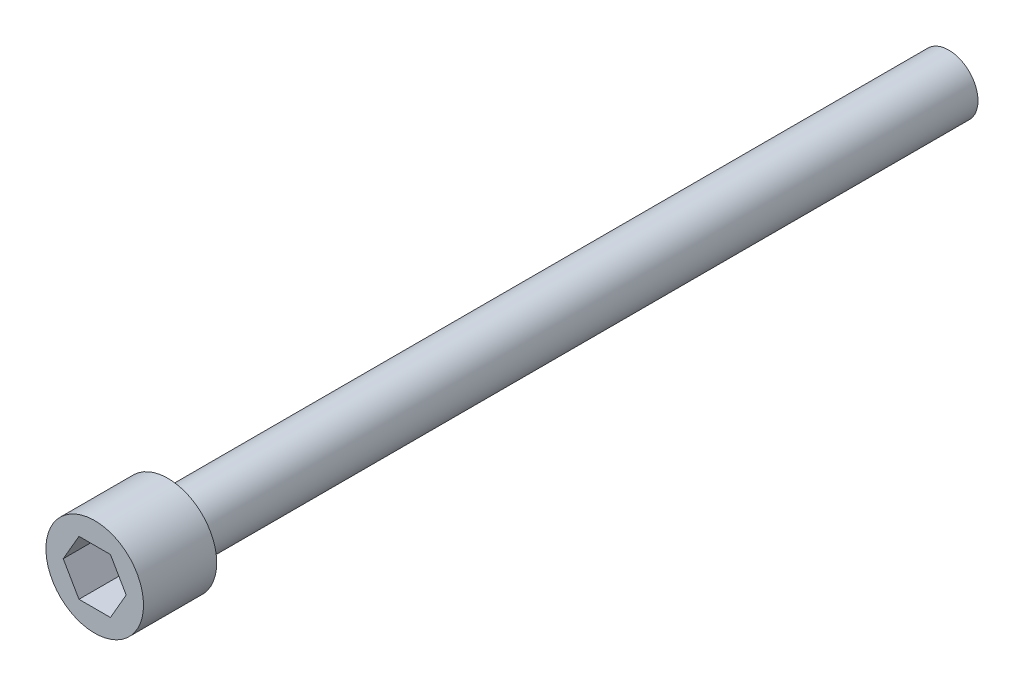
SolidWorks part; units mm, degrees
ref_plane "Front Plane" through (0, 0, 0) normal (0, 0, 1) x (1, 0, 0)
ref_plane "Top Plane" through (0, 0, 0) normal (0, 1, 0) x (1, 0, 0)
ref_plane "Right Plane" through (0, 0, 0) normal (1, 0, 0) x (0, 0, -1)
sketch "Sketch1" plane through (0, 0, 0) normal (0, 0, 1) x (1, 0, 0)
  circle A0 centre (-15, 15) radius 1.2
extrude "Boss-Extrude1" add sketch "Sketch1" against normal blind 32
sketch "Sketch2" plane through (0, 0, 0) normal (0, 0, 1) x (1, 0, 0)
  circle A0 centre (-15, 15) radius 2
extrude "Boss-Extrude2" add sketch "Sketch2" along normal blind 3
sketch "Sketch3" plane through (0, 0, 3) normal (0, 0, 1) x (1, 0, 0)
  line L1 (-13.7099, 15) -> (-14.355, 16.1172)
  line L2 (-14.355, 16.1172) -> (-15.645, 16.1172)
  line L3 (-15.645, 16.1172) -> (-16.2901, 15)
  line L4 (-16.2901, 15) -> (-15.645, 13.8828)
  line L5 (-15.645, 13.8828) -> (-14.355, 13.8828)
  line L6 (-14.355, 13.8828) -> (-13.7099, 15)
  circle A0 centre (-15, 15) radius 1.1172 construction
extrude "Cut-Extrude1" cut sketch "Sketch3" against normal blind 2
